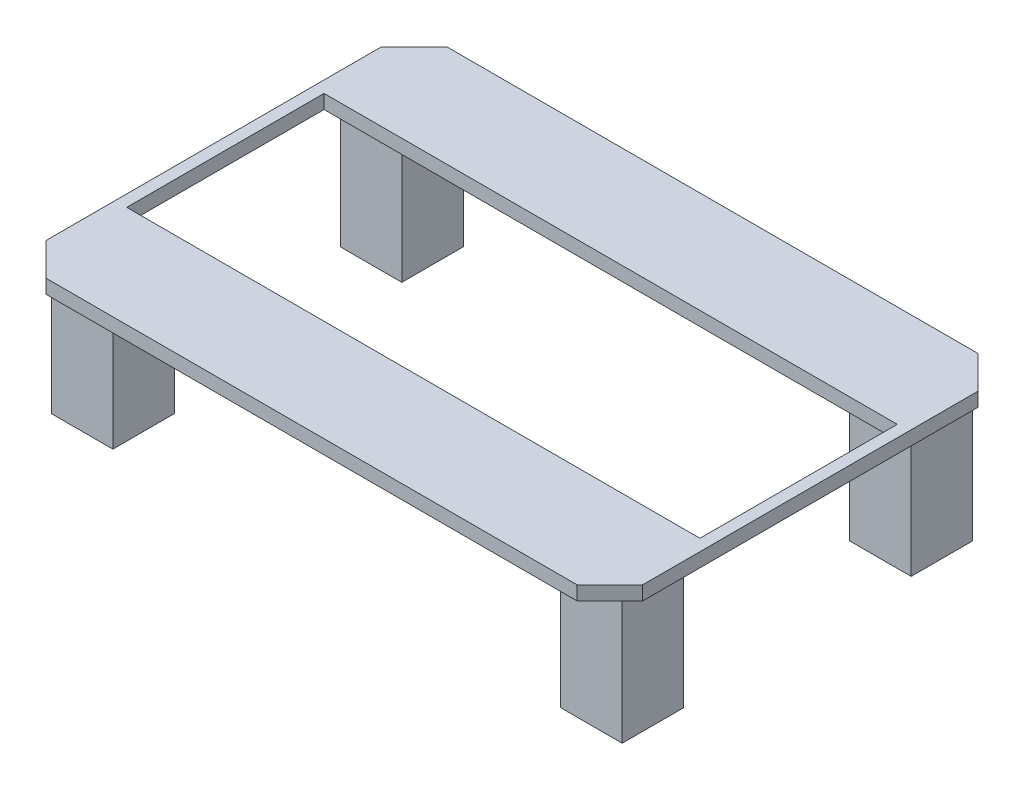
SolidWorks part; units mm, degrees
ref_plane "Front Plane" through (0, 0, 0) normal (0, 0, 1) x (1, 0, 0)
ref_plane "Top Plane" through (0, 0, 0) normal (0, 1, 0) x (1, 0, 0)
ref_plane "Right Plane" through (0, 0, 0) normal (1, 0, 0) x (0, 0, -1)
sketch "Sketch1" plane through (0, 0, 0) normal (0, 1, 0) x (1, 0, 0)
  line L1 (-64, -43) -> (64, -43)
  line L2 (-64, -43) -> (-64, 43)
  line L3 (-64, 43) -> (64, 43)
  line L4 (64, -43) -> (64, 43)
  line L5 (-64, -43) -> (64, 43) construction
  line L6 (-64, 43) -> (64, -43) construction
  point P0 (0, 0)
  dimension "D1" = 128
  dimension "D2" = 90
  dimension "D3" = 86
extrude "Boss-Extrude1" add sketch "Sketch1" along normal blind 3
sketch "Sketch3" plane through (0, 0, 0) normal (0, -1, 0) x (-1, 0, 0)
  line L0 (64, -43) -> (56.9994, -43)
  line L1 (64, -43) -> (-64, -43) construction
  line L2 (56.9994, -43) -> (64, -35.9957)
  line L3 (64, 43) -> (64, -43) construction
  line L4 (64, -35.9957) -> (64, -43)
extrude "Cut-Extrude1" cut sketch "Sketch3" against normal blind 3
sketch "Sketch6" plane through (0, 0, 0) normal (0, -1, 0) x (1, 0, 0)
  line L0 (-64, -43) -> (-57, -43)
  line L1 (64, -43) -> (-64, -43) construction
  line L2 (-57, -43) -> (-64, -36.0033)
  line L3 (-64, -43) -> (-64, 35.9957) construction
  line L4 (-64, -36.0033) -> (-64, -43)
  dimension "D1" = 6.9967
extrude "Cut-Extrude2" cut sketch "Sketch6" against normal blind 3
sketch "Sketch7" plane through (0, 0, 0) normal (0, -1, 0) x (1, 0, 0)
  line L0 (64, 43) -> (57, 43)
  line L1 (-56.9994, 43) -> (64, 43) construction
  line L2 (57, 43) -> (64, 36)
  line L3 (64, 43) -> (64, -43) construction
  line L4 (64, 36) -> (64, 43)
  dimension "D1" = 7
  dimension "D2" = 7
extrude "Cut-Extrude3" cut sketch "Sketch7" against normal blind 3
sketch "Sketch8" plane through (0, 0, 0) normal (0, -1, 0) x (1, 0, 0)
  line L0 (64, -43) -> (64, -36)
  line L1 (64, 36) -> (64, -43) construction
  line L2 (64, -36) -> (57, -43)
  line L3 (64, -43) -> (-57, -43) construction
  line L4 (57, -43) -> (64, -43)
  dimension "D1" = 7
  dimension "D2" = 7
extrude "Cut-Extrude4" cut sketch "Sketch8" against normal blind 3
sketch "Sketch9" plane through (0, 0, 0) normal (0, -1, 0) x (1, 0, 0)
  line L1 (-61.5, 21.175) -> (61.5, 21.175)
  line L2 (-61.5, 21.175) -> (-61.5, -21.175)
  line L3 (-61.5, -21.175) -> (61.5, -21.175)
  line L4 (61.5, 21.175) -> (61.5, -21.175)
  line L5 (-61.5, 21.175) -> (61.5, -21.175) construction
  line L6 (-61.5, -21.175) -> (61.5, 21.175) construction
  point P0 (0, 0)
  dimension "D1" = 123
  dimension "D2" = 42.35
extrude "Cut-Extrude5" cut sketch "Sketch9" against normal blind 3
sketch "Sketch23" plane through (0, 0, 0) normal (0, -1, 0) x (1, 0, 0)
  line L1 (61.2513, 24.4005) -> (48.0513, 24.4005)
  line L2 (61.2513, 24.4005) -> (61.2513, 37.6005)
  line L3 (61.2513, 37.6005) -> (48.0513, 37.6005)
  line L4 (48.0513, 24.4005) -> (48.0513, 37.6005)
  dimension "D1" = 13.2
  dimension "D2" = 13.2
extrude "Boss-Extrude7" add sketch "Sketch23" along normal blind 27
mirror "Mirror1" about plane through (0, 0, 0) normal (0, 0, 1) of "Boss-Extrude7"
mirror "Mirror2" about plane through (0, 0, 0) normal (1, 0, 0) of "Mirror1", "Boss-Extrude7"
sketch "Sketch25" plane through (0, 0, 0) normal (0, -1, 0) x (1, 0, 0)
  line L0 (-48.0513, -37.6005) -> (-48.0513, -24.4005) construction
  line L1 (-48.0513, -24.4853) -> (-39.4513, -24.4853)
  line L2 (-48.0513, -24.4853) -> (-48.0513, -31.5853)
  line L3 (-48.0513, -31.5853) -> (-39.4513, -31.5853)
  line L4 (-39.4513, -24.4853) -> (-39.4513, -31.5853)
  line L5 (-48.0513, -37.6005) -> (-48.0513, -24.4005) construction
  dimension "D1" = 8.6
  dimension "D2" = 7.1
extrude "Boss-Extrude8" add sketch "Sketch25" along normal blind 3
mirror "Mirror4" about plane through (0, 0, 0) normal (0, 0, 1) of "Boss-Extrude8"
